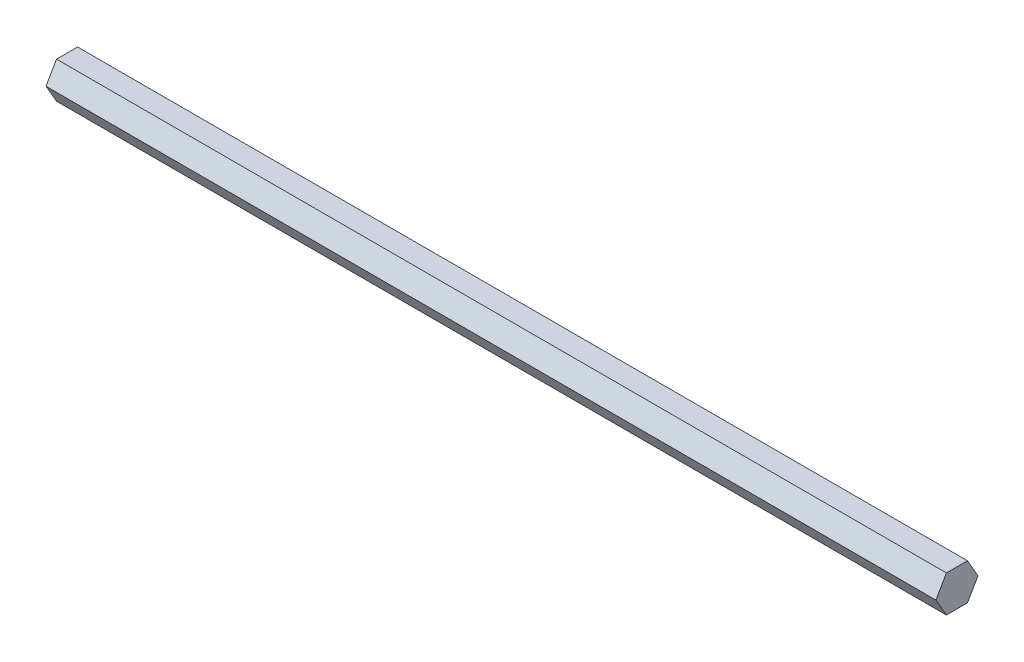
SolidWorks part; units mm, degrees
ref_plane "Alzado" through (0, 0, 0) normal (0, 0, 1) x (1, 0, 0)
ref_plane "Planta" through (0, 0, 0) normal (0, 1, 0) x (1, 0, 0)
ref_plane "Vista lateral" through (0, 0, 0) normal (1, 0, 0) x (0, 0, -1)
sketch "Croquis1" plane through (0, 0, 0) normal (1, 0, 0) x (0, 0, -1)
  line L1 (7.3323, 0) -> (3.6662, 6.35)
  line L2 (3.6662, 6.35) -> (-3.6662, 6.35)
  line L3 (-3.6662, 6.35) -> (-7.3323, 0)
  line L4 (-7.3323, 0) -> (-3.6662, -6.35)
  line L5 (-3.6662, -6.35) -> (3.6662, -6.35)
  line L6 (3.6662, -6.35) -> (7.3323, 0)
  circle A0 centre (0, 0) radius 6.35 construction
  dimension "D1" = 12.7
extrude "Saliente-Extruir1" add sketch "Croquis1" along normal blind 310
